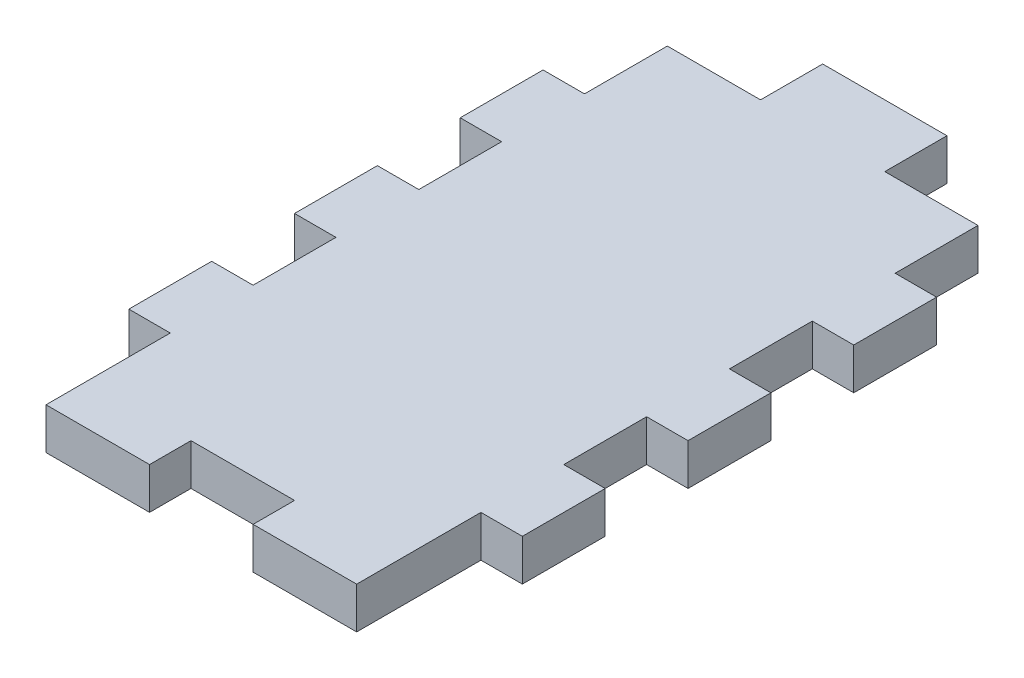
SolidWorks part; units mm, degrees
ref_plane "Front Plane" through (0, 0, 0) normal (0, 0, 1) x (1, 0, 0)
ref_plane "Top Plane" through (0, 0, 0) normal (0, 1, 0) x (1, 0, 0)
ref_plane "Right Plane" through (0, 0, 0) normal (1, 0, 0) x (0, 0, -1)
other "Configuration Table"
sketch "Sketch1" plane through (0, 0, 0) normal (0, 1, 0) x (1, 0, 0)
  line L0 (0, 30) -> (0, -30) construction
  line L5 (-15, 30) -> (15, -30) construction
  line L6 (-15, -30) -> (15, 30) construction
  line L7 (-15, 22) -> (-19, 22)
  line L9 (-15, 14) -> (-19, 14)
  line L10 (-19, 22) -> (-19, 14)
  line L11 (-15, 6) -> (-19, 6)
  line L13 (-15, -2) -> (-19, -2)
  line L14 (-19, 6) -> (-19, -2)
  line L15 (-15, -18) -> (-15, -26)
  line L16 (-15, -10) -> (-19, -10)
  line L18 (-15, -18) -> (-19, -18)
  line L19 (-19, -10) -> (-19, -18)
  line L32 (-15, -26) -> (-15, -30)
  line L33 (-5, -26) -> (5, -26)
  line L34 (-5, -26) -> (-5, -30)
  line L36 (5, -26) -> (5, -30)
  line L40 (15, -26) -> (15, -30)
  line L41 (-15, -10) -> (-15, -2)
  line L42 (-15, 6) -> (-15, 14)
  line L43 (-15, 22) -> (-15, 30)
  line L44 (-15, -30) -> (-5, -30)
  line L45 (5, -30) -> (15, -30)
  line L47 (-15, 30) -> (-6, 30)
  line L49 (-6, 30) -> (-6, 36)
  line L50 (-6, 36) -> (6, 36)
  line L51 (6, 30) -> (6, 36)
  line L52 (6, 30) -> (15, 30)
  line L53 (15, -18) -> (15, -26)
  line L54 (15, -18) -> (19, -18)
  line L55 (19, -10) -> (19, -18)
  line L56 (15, -10) -> (19, -10)
  line L57 (15, -10) -> (15, -2)
  line L58 (15, -2) -> (19, -2)
  line L59 (19, 6) -> (19, -2)
  line L60 (15, 6) -> (19, 6)
  line L61 (15, 6) -> (15, 14)
  line L62 (15, 14) -> (19, 14)
  line L63 (19, 22) -> (19, 14)
  line L64 (15, 22) -> (19, 22)
  line L65 (15, 22) -> (15, 30)
  point P0 (0, 0)
  dimension "D1" = 60
  dimension "D2" = 30
  dimension "D3" = 8
  dimension "D4" = 8
  dimension "D5" = 4
  dimension "D6" = 4
  dimension "D7" = 8
  dimension "D8" = 8
  dimension "D9" = 8
  dimension "D10" = 12
  dimension "D11" = 10
  dimension "D12" = 10
  dimension "D13" = 10
  dimension "D14" = 6
extrude "Boss-Extrude2" add sketch "Sketch1" along normal blind 4
